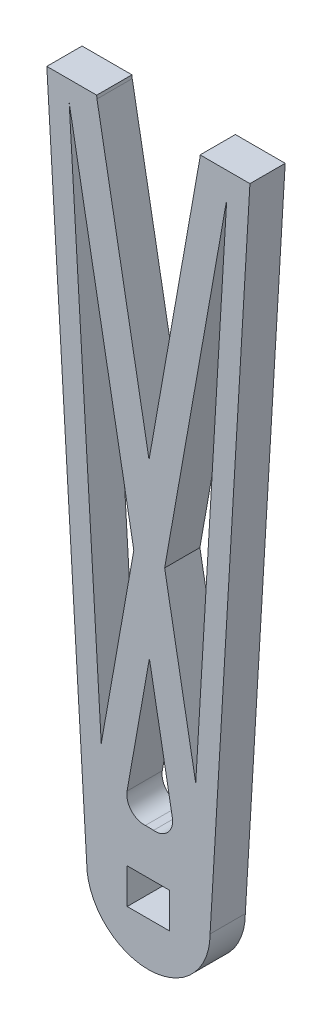
SolidWorks part; units mm, degrees
ref_plane "Front Plane" through (0, 0, 0) normal (0, 0, 1) x (1, 0, 0)
ref_plane "Top Plane" through (0, 0, 0) normal (0, 1, 0) x (1, 0, 0)
ref_plane "Right Plane" through (0, 0, 0) normal (1, 0, 0) x (0, 0, -1)
sketch "Sketch1" plane through (0, 0, 0) normal (0, 0, 1) x (1, 0, 0)
  line L0 (-30, 0) -> (30, 0)
  line L1 (0, 0) -> (15, 0)
  line L2 (55, 0) -> (-55, 0) construction
  line L3 (0, 0) -> (0, -210)
  line L4 (0, -44.7868) -> (0, 44.7868) construction
  line L5 (0, 0) -> (30, 0)
  line L6 (0, 0) -> (-30, 0)
  line L7 (0, 0) -> (-15, 0)
  line L8 (-6, -215) -> (6, -215)
  line L9 (-6, -215) -> (-6, -205)
  line L10 (-6, -205) -> (6, -205)
  line L11 (6, -215) -> (6, -205)
  line L12 (-6, -215) -> (6, -205) construction
  line L13 (-6, -205) -> (6, -215) construction
  line L14 (0, 0) -> (0, 15)
  line L15 (-30, 0) -> (-17.5, -210)
  line L16 (-30, 0) -> (30, 0)
  line L17 (-30, 0) -> (-30, 15.7704)
  line L18 (-30, 15.7704) -> (30, 15.7704)
  line L19 (30, 0) -> (30, 15.7704)
  line L20 (30, 0) -> (17.5, -210)
  circle A0 centre (15, 0) radius 3
  circle A1 centre (-15, 0) radius 3
  circle A2 centre (0, -210) radius 17.5
  point P4 (0, 0)
  dimension "D7" = 6
  dimension "D9" = 6
  dimension "D11" = 35
  dimension "D1" = 210
  dimension "D2" = 30
  dimension "D3" = 30
  dimension "D4" = 10
  dimension "D5" = 12
  dimension "D6" = 15
  dimension "D8" = 15
  dimension "D10" = 15
extrude "Boss-Extrude2" add sketch "Sketch1" along normal blind 10
fillet "Fillet1" radius 20 1 edges at (-30, 15.7704, 5)
fillet "Fillet2" radius 20 1 edges at (30, 15.7704, 5)
sketch "Sketch4" plane through (0, 0, 10) normal (0, 0, 1) x (1, 0, 0)
  line L0 (-29.3398, -11.0918) -> (-23.3398, -11.0918)
  line L1 (-29.6775, -5.418) -> (-17.5, -210) construction
  line L2 (29.3911, -10.23) -> (23.3911, -10.23)
  line L3 (29.6775, -5.418) -> (17.5, -210) construction
  line L4 (-18.3824, -195.1758) -> (-12.3824, -195.1758)
  line L5 (18.3824, -195.1758) -> (12.3824, -195.1758)
  line L6 (-12.3824, -195.1758) -> (-23.5439, -7.6624)
  line L7 (23.3911, -7.6624) -> (11.6198, -205.4193)
  line L8 (-22.9543, -15) -> (22.9543, -15)
  line L9 (-8.4362, -200.1287) -> (-16.4545, -196.0413)
  line L10 (9.2183, -200.015) -> (17.2308, -195.9163)
  line L11 (9.2183, -200.015) -> (-24.5465, -14.245)
  line L12 (17.2308, -195.9163) -> (-16.534, -10.1463)
  line L13 (-24.5465, -14.245) -> (-16.534, -10.1463)
  line L14 (-8.4362, -200.1287) -> (24.4903, -14.4152)
  line L15 (-16.4545, -196.0413) -> (16.472, -10.3277)
  line L16 (24.4903, -14.4152) -> (16.472, -10.3277)
  circle A0 centre (0, -210) radius 17.5
  circle A1 centre (15, 0) radius 15
  point P25 (0, -15)
  dimension "D5" = 15
  dimension "D1" = 6
  dimension "D2" = 6
  dimension "D3" = 6
  dimension "D4" = 6
  dimension "D6" = 9
  dimension "D7" = 9
extrude "Cut-Extrude1" cut sketch "Sketch4" against normal blind 10 contours L12 L15 L8 | L6 L15 L11 | L14 L12 L7 | A0 L11 L14
fillet "Fillet3" radius 5 4 edges at (8.2256, -194.5537, 5) (-7.3724, -194.1287, 5) (-15.6518, -15, 5) (15.6436, -15, 5)
sketch "Sketch5" plane through (0, 0, 10) normal (0, 0, 1) x (1, 0, 0)
  line L0 (15, 0) -> (30, 0)
  line L1 (55, 0) -> (-55, 0) construction
  line L2 (30, 0) -> (30, -20)
  line L3 (0, -175.7959) -> (34.2041, -175.7959)
  line L5 (30, -20) -> (30, 0)
  line L8 (0, -175.7959) -> (-19.536, -175.7959)
  line L9 (-29.6775, -5.418) -> (-17.5, -210) construction
  line L12 (30, 0) -> (20, 0)
  line L17 (30, 0) -> (30, 24.03)
  line L18 (30, 24.03) -> (20, 24.03)
  line L19 (20, 0) -> (20, 24.03)
  line L20 (30, 0) -> (20, 0)
  line L21 (30, 0) -> (30, -20)
  line L22 (30, -20) -> (20, -20)
  line L23 (20, 0) -> (20, -20)
  circle A0 centre (0, -210) radius 30
  circle A1 centre (0, -210) radius 34.2041
  circle A2 centre (0, -210) radius 36
  line M1 (17.5, -210) -> (29.6775, -5.418)
  arc M2 (29.6775, -5.418) -> (9.7128, 15.7704) centre (9.7128, -4.2296) ccw
  dimension "D3" = 60
  dimension "D4" = 36
  dimension "D1" = 15
  dimension "D2" = 20
  dimension "D5" = 24.03
  dimension "D6" = 10
  dimension "D7" = 20
  dimension "D8" = 10
extrude "Cut-Extrude6" cut sketch "Sketch5" against normal blind 10 contours L0 L23 L22 M1 M2 | L19 L0 M2
sketch "Sketch7" plane through (0, 0, 10) normal (0, 0, 1) x (1, 0, 0)
  line L1 (28.8095, -20) -> (-36.2009, -20)
  line L2 (28.8095, -20) -> (28.8095, 18.0338)
  line L3 (28.8095, 18.0338) -> (-36.2009, 18.0338)
  line L4 (-36.2009, -20) -> (-36.2009, 18.0338)
extrude "Cut-Extrude7" cut sketch "Sketch7" against normal blind 10
